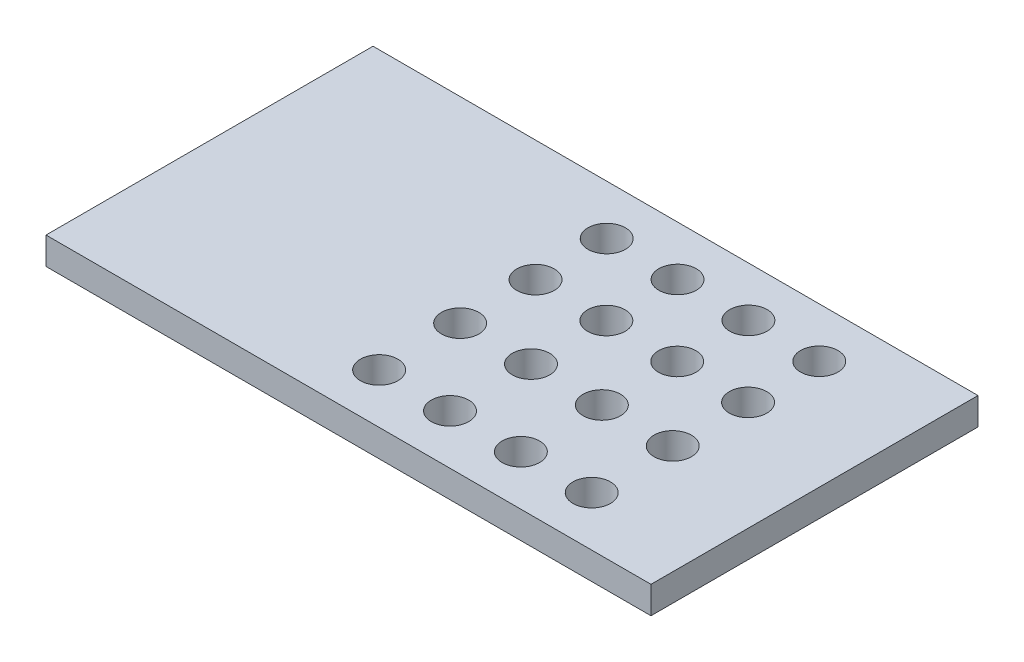
SolidWorks part; units mm, degrees
ref_plane "Front Plane" through (0, 0, 0) normal (0, 0, 1) x (1, 0, 0)
ref_plane "Top Plane" through (0, 0, 0) normal (0, 1, 0) x (1, 0, 0)
ref_plane "Right Plane" through (0, 0, 0) normal (1, 0, 0) x (0, 0, -1)
sketch "Sketch1" plane through (0, 0, 0) normal (0, 1, 0) x (1, 0, 0)
  line L0 (-90.805, 25.367) -> (50.165, 25.367) construction
  line L1 (50.165, -39.2443) -> (-90.805, -39.2443)
  line L2 (50.165, -39.2443) -> (50.165, 36.9557)
  line L3 (50.165, 36.9557) -> (-90.805, 36.9557)
  line L4 (-90.805, -39.2443) -> (-90.805, 36.9557)
  line L5 (-8.255, 8.7808) -> (8.255, -8.7808) construction
  line L6 (-78.105, 36.9557) -> (-78.105, 25.367) construction
  line L7 (50.165, 8.7808) -> (-90.805, 8.7808) construction
  line L8 (-90.805, -27.6555) -> (50.165, -27.6555) construction
  line L9 (50.165, -8.7808) -> (-90.805, -8.7808) construction
  line L10 (-24.765, -39.2443) -> (-24.765, 36.9557) construction
  line L11 (-8.255, 36.9557) -> (-8.255, -39.2443) construction
  line L12 (8.255, -39.2443) -> (8.255, 36.9557) construction
  line L13 (24.765, 36.9557) -> (24.765, -39.2443) construction
  line L14 (-78.105, -27.6555) -> (-78.105, -39.2443) construction
  circle A0 centre (-24.765, 25.367) radius 4.3656
  circle A1 centre (-8.255, 25.367) radius 4.3656
  circle A2 centre (8.255, 25.367) radius 4.3656
  circle A3 centre (24.765, 25.367) radius 4.3656
  circle A4 centre (24.765, 8.7808) radius 4.3656
  circle A5 centre (8.255, 8.7808) radius 4.3656
  circle A6 centre (-8.255, 8.7808) radius 4.3656
  circle A7 centre (-24.765, 8.7808) radius 4.3656
  circle A8 centre (-24.765, -8.7808) radius 4.3656
  circle A9 centre (-8.255, -8.7808) radius 4.3656
  circle A10 centre (8.255, -8.7808) radius 4.3656
  circle A11 centre (24.765, -8.7808) radius 4.3656
  circle A12 centre (24.765, -27.6555) radius 4.3656
  circle A13 centre (8.255, -27.6555) radius 4.3656
  circle A14 centre (-8.255, -27.6555) radius 4.3656
  circle A15 centre (-24.765, -27.6555) radius 4.3656
  point P0 (0, 0)
  point P22 (-24.765, 25.367)
  point P23 (-8.255, 25.367)
  point P24 (8.255, 25.367)
  point P25 (24.765, 25.367)
  point P26 (24.765, 8.7808)
  point P27 (24.765, -8.7808)
  point P28 (24.765, -27.6555)
  point P29 (8.255, -27.6555)
  point P30 (-8.255, -27.6555)
  point P31 (-24.765, -27.6555)
  point P32 (-24.765, -8.7808)
  point P33 (-8.255, -8.7808)
  point P34 (8.255, -8.7808)
  point P35 (8.255, 8.7808)
  point P36 (-8.255, 8.7808)
  point P37 (-24.765, 8.7808)
  dimension "D11" = 8.7312
  dimension "D9" = 16.51
  dimension "D10" = 16.51
  dimension "D4" = 16.5862
  dimension "D15" = 18.8747
  dimension "D3" = 16.51
  dimension "D6" = 25.4
  dimension "D7" = 76.2
  dimension "D5" = 17.5616
  dimension "D8" = 140.97
  dimension "D2" = 12.7
extrude "Boss-Extrude1" add sketch "Sketch1" along normal blind 6.35
equation "\"D2@Sketch1\"=0.5"
